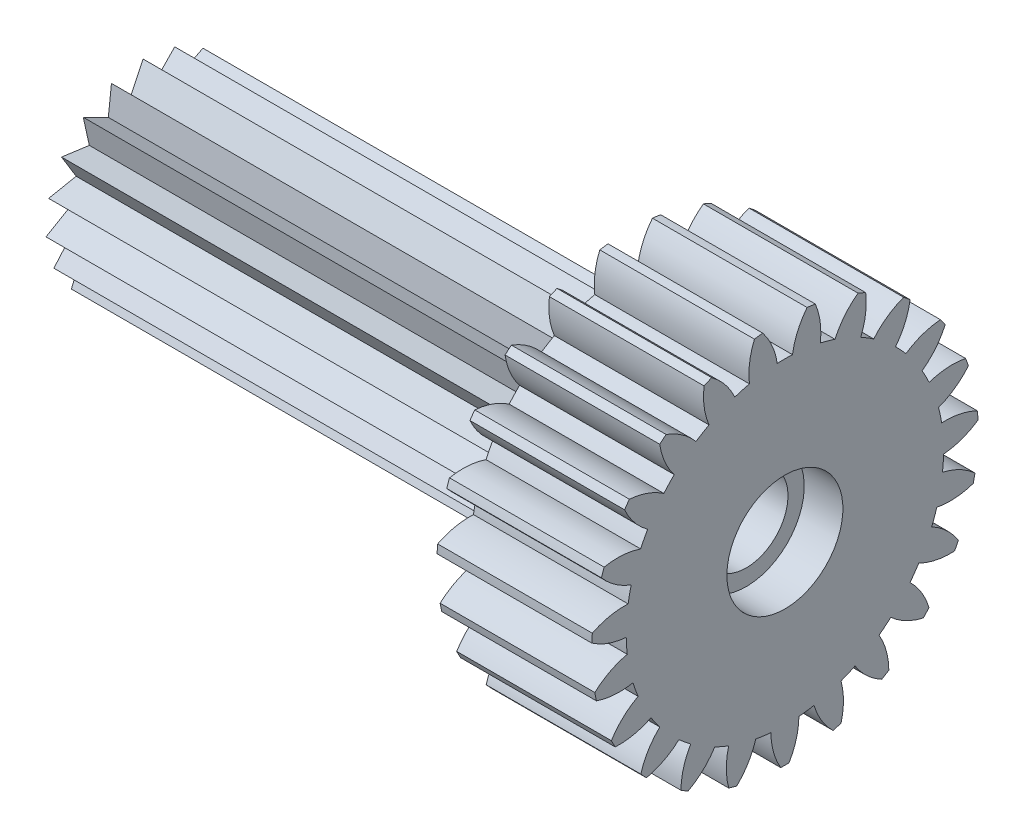
SolidWorks part; units mm, degrees
ref_plane "Plane1" through (0, 0, 0) normal (0, 0, 1) x (1, 0, 0)
ref_plane "Plane2" through (0, 0, 0) normal (0, 1, 0) x (1, 0, 0)
ref_plane "Plane3" through (0, 0, 0) normal (1, 0, 0) x (0, 0, -1)
other "Configuration Table"
sketch "HoldingSke" plane through (0, 0, 0) normal (0, 1, 0) x (1, 0, 0)
  line L0 (0, 0) -> (467.6165, -198.4914)
  line L1 (-15, 0) -> (100, 0) construction
  line L2 (0, 0) -> (-2.1039, 2.3779)
  line L3 (0, 0) -> (-11.863, 4.5341)
  line L4 (0, 0) -> (7.9495, 3.3744)
  line L5 (0, 0) -> (-47.5972, -17.7524)
  line L6 (0, 0) -> (-7.3695, -4.9722)
  line L7 (-2.1039, 2.3779) -> (8.8308, 51.9871)
  line L8 (-76.2, 54.61) -> (-69.596, 54.61)
  line L9 (-71.009, 38.7566) -> (-53.1078, 45.2721)
  line L10 (-76.2, 71.12) -> (104.1128, 71.12)
  line L11 (0, 0) -> (-8.89, 0)
  line L12 (-76.2, 101.6) -> (-76.1492, 101.6)
  line L13 (24.9733, 27.94) -> (52.9518, 28.4284)
  line L14 (24.9733, 27.94) -> (25.0241, 27.9398)
  line L15 (24.9733, 27.94) -> (100.4021, 29.52)
  circle A0 centre (0, 0) radius 3.175
  circle A1 centre (0, 0) radius 13.0302
  circle A2 centre (0, 0) radius 38.1
  circle A3 centre (0, 0) radius 3.175
  dimension "MHD" = 26.0604
  dimension "Hub_dia" = 76.2
  dimension "Bore" = 6.35
  dimension "MBD" = 6.35
  dimension "Num_teeth" = 23
  dimension "Pitch" = 508
  dimension "Overall_len" = 50.8
  dimension "Show_teeth" = 23
  dimension "Thickness" = 8.89
  dimension "OAL" = 50.8001
  dimension "T_dim" = 6.604
  dimension "Ap" = 20
  dimension "H" = 19.05
  dimension "Pitch_radius" = 180.3128
  dimension "Width" = 8.89
  dimension "Backlash" = 0.0508
  dimension "Addendum_fac" = 1
  dimension "Dedendum_fac" = 1.2
  dimension "Clearance_fac" = 0.2
  dimension "Dedendum_add" = 0.0508
sketch "BasProSke" plane through (0, 0, 0) normal (0, 1, 0) x (1, 0, 0)
  line L0 (-10, 0) -> (60, 0) construction
  line L1 (0, 0) -> (0, 15.875)
  line L2 (0, 0) -> (12.7, 0)
  line L3 (12.7, 0) -> (12.7, 15.875)
  line L4 (12.7, 15.875) -> (0, 15.875)
  dimension "Thickness" = 12.7
  dimension "Diameter" = 31.75
revolve "Base-Revolve" add sketch "BasProSke" angle 360 about L0
sketch "TooCutSke" plane through (0, 0, 0) normal (1, 0, 0) x (0, 0, -1)
  line L1 (0, 0) -> (0, 107) construction
  line L2 (0, 0) -> (-1.0855, 14.5646) construction
  line L3 (0, 0) -> (-3.9697, 28.882) construction
  line L4 (-1.0855, 14.5646) -> (-1.9849, 14.441) construction
  arc A0 (0.6246, 13.0152) -> (-0.6246, 13.0152) centre (0, 0) ccw
  arc A1 (1.8419, 15.7934) -> (-1.8419, 15.7934) centre (0, 0) ccw
  circle A2 centre (0, 0) radius 14.605 construction
  circle A3 centre (0, 0) radius 13.7242 construction
  arc A4 (-0.6246, 13.0152) -> (-1.8419, 15.7934) centre (-6.4007, 12.1402) ccw
  arc A5 (1.8419, 15.7934) -> (0.6246, 13.0152) centre (6.4007, 12.1402) ccw
  dimension "Root_dia" = 26.0604
  dimension "Overcut_dia" = 31.8008
  dimension "Pitch_dia" = 29.21
  dimension "Base_dia" = 27.4484
  dimension "Flank_rad" = 5.842
  dimension "Half_ang" = 7.826
  dimension "Half_CT" = 0.9078
extrude "ToothCut" cut sketch "TooCutSke" along normal through all
fillet "Breaks" [suppressed] radius 0.0254
fillet "RootFillets" [suppressed] radius 0.3048
pattern_circular "TeethCuts" count 23 every 15.652 about axis through (-10, 0, 0) along (1, 0, 0) of "ToothCut", "RootFillets", "Breaks"
sketch "HubNeaOneSke" plane through (0, 0, 0) normal (-1, 0, 0) x (0, 0, 1)
  circle A0 centre (0, 0) radius 13.0302
  dimension "Diameter" = 26.0604
extrude "HubNearOne" [suppressed] add sketch "HubNeaOneSke" along normal blind 38.1001
sketch "HubNeaBotSke" plane through (0, 0, 0) normal (-1, 0, 0) x (0, 0, 1)
  circle A0 centre (0, 0) radius 13.0302
  dimension "Diameter" = 26.0604
extrude "HubNearBoth" [suppressed] add sketch "HubNeaBotSke" along normal blind 19.05
ref_plane "FarPln" through (12.7, 0, 0) normal (1, 0, 0) x (0, 0, -1)
sketch "HubFarSke" plane through (12.7, 0, 0) normal (1, 0, 0) x (0, 0, -1)
  circle A0 centre (0, 0) radius 13.0302
  dimension "Diameter" = 26.0604
extrude "HubFar" [suppressed] add sketch "HubFarSke" along normal blind 19.05
sketch "BorSke" plane through (0, 0, 0) normal (1, 0, 0) x (0, 0, -1)
  circle A0 centre (0, 0) radius 4.7625
  dimension "Diameter" = 9.525
extrude "Bore" cut sketch "BorSke" along normal mid plane 101.6001
sketch "KeySke" plane through (0, 0, 0) normal (1, 0, 0) x (0, 0, -1)
  line L0 (-0.127, 0) -> (-0.127, 3.429)
  line L1 (-0.127, 3.429) -> (0.127, 3.429)
  line L2 (0.127, 3.429) -> (0.127, 0)
  line L3 (0, 0) -> (0, 34) construction
  line L4 (-0.127, 0) -> (0.127, 0)
  dimension "Offset" = 3.429
  dimension "Width" = 0.254
extrude "Keyway" [suppressed] cut sketch "KeySke" along normal mid plane 101.6001
pattern_circular "Keyway2" [suppressed] count 2 every 90 about axis through (-10, 0, 0) along (1, 0, 0)
sketch "Sketch2" plane through (0, 0, 0) normal (-1, 0, 0) x (0, 0, 1)
  line L0 (2.5976, 7.5665) -> (2.8557, 5.2768)
  line L1 (-0.9876, 5.9182) -> (0, 8)
  line L2 (0, 8) -> (0.9876, 5.9182)
  line L3 (0.9876, 5.9182) -> (2.5976, 7.5665)
  line L4 (4.9137, 6.3131) -> (4.4143, 4.0637)
  line L5 (2.8557, 5.2768) -> (4.9137, 6.3131)
  line L6 (6.6973, 4.3756) -> (5.4946, 2.4102)
  line L7 (4.4143, 4.0637) -> (6.6973, 4.3756)
  line L8 (7.7552, 1.9639) -> (5.9795, 0.4955)
  line L9 (5.4946, 2.4102) -> (7.7552, 1.9639)
  line L10 (7.9727, -0.6606) -> (5.8164, -1.4729)
  line L11 (5.9795, 0.4955) -> (7.9727, -0.6606)
  line L12 (7.3262, -3.2136) -> (5.023, -3.2817)
  line L13 (5.8164, -1.4729) -> (7.3262, -3.2136)
  line L14 (5.8858, -5.4183) -> (3.6853, -4.7348)
  line L15 (5.023, -3.2817) -> (5.8858, -5.4183)
  line L16 (3.8076, -7.0358) -> (1.9482, -5.6749)
  line L17 (3.6853, -4.7348) -> (3.8076, -7.0358)
  line L18 (1.3168, -7.8909) -> (0, -6)
  line L19 (1.9482, -5.6749) -> (1.3168, -7.8909)
  line L20 (-1.3168, -7.8909) -> (-1.9482, -5.6749)
  line L21 (0, -6) -> (-1.3168, -7.8909)
  line L22 (-3.8076, -7.0358) -> (-3.6853, -4.7348)
  line L23 (-1.9482, -5.6749) -> (-3.8076, -7.0358)
  line L24 (-5.8858, -5.4183) -> (-5.023, -3.2817)
  line L25 (-3.6853, -4.7348) -> (-5.8858, -5.4183)
  line L26 (-7.3262, -3.2136) -> (-5.8164, -1.4729)
  line L27 (-5.023, -3.2817) -> (-7.3262, -3.2136)
  line L28 (-7.9727, -0.6606) -> (-5.9795, 0.4955)
  line L29 (-5.8164, -1.4729) -> (-7.9727, -0.6606)
  line L30 (-7.7552, 1.9639) -> (-5.4946, 2.4102)
  line L31 (-5.9795, 0.4955) -> (-7.7552, 1.9639)
  line L32 (-6.6973, 4.3756) -> (-4.4143, 4.0637)
  line L33 (-5.4946, 2.4102) -> (-6.6973, 4.3756)
  line L34 (-4.9137, 6.3131) -> (-2.8557, 5.2768)
  line L35 (-4.4143, 4.0637) -> (-4.9137, 6.3131)
  line L36 (-2.5976, 7.5665) -> (-0.9876, 5.9182)
  line L37 (-2.8557, 5.2768) -> (-2.5976, 7.5665)
  circle A0 centre (0, 0) radius 6 construction
  circle A1 centre (0, 0) radius 3.429
  point P62 (0, 0)
  dimension "D1" = 12
  dimension "D4" = 6.858
  dimension "D2" = 8
  dimension "D3" = 19
extrude "Boss-Extrude1" add sketch "Sketch2" along normal blind 40 and the other way blind 9.525
sketch "Sketch3" plane through (-40, 0, 0) normal (-1, 0, 0) x (0, 0, 1)
  circle A0 centre (0, 0) radius 4.7625
  dimension "D1" = 9.525
extrude "Cut-Extrude1" cut sketch "Sketch3" against normal blind 3.175
equation "' \"Pitch@HoldingSke\" = 4"
equation "' \"Num_teeth@HoldingSke\" = 12"
equation "' \"Ap@HoldingSke\" =  20"
equation "' \"Ap@HoldingSke\" = 20"
equation "' \"Width@HoldingSke\" = 0.5"
equation "' \"Hub_dia@HoldingSke\"= 1"
equation "' \"Hub_dia@HoldingSke\" = 1"
equation "' \"Overall_len@HoldingSke\" = 1.0"
equation "' \"Bore@HoldingSke\" = 0.75"
equation "' \"T_dim@HoldingSke\" = 0.85"
equation "' \"Width@KeySke\" = 0.25"
equation "' \"Show_teeth@HoldingSke\" = 13"
equation "' \"Backlash@HoldingSke\" = 0.009"
equation "' \"Addendum_fac@HoldingSke\" = 1.0"
equation "' \"Dedendum_fac@HoldingSke\" = 1.25"
equation "' \"Dedendum_add@HoldingSke\" = 0.00005"
equation "' \"Clearance_fac@HoldingSke\" = 0.25"
equation "' \"Pitch@HoldingSke\" = 0.5"
equation "' \"Num_teeth@HoldingSke\" = 23"
equation "' \"Show_teeth@HoldingSke\" = 23"
equation "' \"Backlash@HoldingSke\" = 0.0375"
equation "\"Overcut_dia@TooCutSke\" = (\"Num_teeth@HoldingSke\" + 2 * \"Addendum_fac@HoldingSke\") / \"Pitch@HoldingSke\" + 0.002"
equation "\"Pitch_dia@TooCutSke\" = \"Num_teeth@HoldingSke\" / \"Pitch@HoldingSke\""
equation "\"Base_dia@TooCutSke\" = \"Num_teeth@HoldingSke\" / \"Pitch@HoldingSke\" * cos((\"Ap@HoldingSke\"  * 3.14159265 / 180))"
equation "\"Root_dia@TooCutSke\" = (\"Num_teeth@HoldingSke\" + 2) / \"Pitch@HoldingSke\" - 2 * (\"Addendum_fac@HoldingSke\" + \"Dedendum_fac@HoldingSke\") / \"Pitch@HoldingSke\" - \"Dedendum_add@HoldingSke\" * 2"
equation "\"Half_ang@TooCutSke\" = 180 / \"Num_teeth@HoldingSke\""
equation "\"Half_CT@TooCutSke\" = \"Num_teeth@HoldingSke\" / \"Pitch@HoldingSke\" * sin((3.14159265 / 2 / \"Num_teeth@HoldingSke\")) / 2 - 7 * \"Backlash@HoldingSke\" / 4"
equation "\"Flank_rad@TooCutSke\" = \"Num_teeth@HoldingSke\" / \"Pitch@HoldingSke\" / 5"
equation "\"Radius@RootFillets\" = \"Clearance_fac@HoldingSke\" / \"Pitch@HoldingSke\" + \"Dedendum_add@HoldingSke\""
equation "\"Break_rad@Breaks\" = 0.02 / \"Pitch@HoldingSke\""
equation "\"Thickness@HoldingSke\" = \"Width@HoldingSke\""
equation "\"OAL@HoldingSke\" = \"Thickness@HoldingSke\""
equation "\"MHD@HoldingSke\" = (\"Num_teeth@HoldingSke\" + 2) / \"Pitch@HoldingSke\" - 2 * (\"Addendum_fac@HoldingSke\" + \"Dedendum_fac@HoldingSke\")  / \"Pitch@HoldingSke\" - \"Dedendum_add@HoldingSke\" * 2"
equation "\"MBD@HoldingSke\" = (\"Num_teeth@HoldingSke\" + 2) / \"Pitch@HoldingSke\" - 2 * (\"Addendum_fac@HoldingSke\" + \"Dedendum_fac@HoldingSke\")  / \"Pitch@HoldingSke\" - \"Dedendum_add@HoldingSke\" * 2 - 0.002"
equation "\"MHD@HoldingSke\" = ((sgn( \"MHD@HoldingSke\" - \"Hub_dia@HoldingSke\" )-1)*( \"MHD@HoldingSke\" - \"Hub_dia@HoldingSke\" ))/-2+ \"Hub_dia@HoldingSke\""
equation "\"MBD@HoldingSke\" = ((sgn( \"MBD@HoldingSke\" - \"Bore@HoldingSke\" )-1)*( \"MBD@HoldingSke\" - \"Bore@HoldingSke\" ))/-2+ \"Bore@HoldingSke\""
equation "\"OAL@HoldingSke\" = ((sgn( \"OAL@HoldingSke\" - \"Overall_len@HoldingSke\" )+1)*( \"OAL@HoldingSke\" - \"Overall_len@HoldingSke\" ))/2 + \"Overall_len@HoldingSke\" + 0.000002"
equation "\"Num_teeth@TeethCuts\" = int( \"Show_teeth@HoldingSke\" ) + 1"
equation "\"Num_teeth@TeethCuts\" = ((sgn( \"Num_teeth@TeethCuts\" - \"Num_teeth@HoldingSke\" )-1)*( \"Num_teeth@TeethCuts\" - \"Num_teeth@HoldingSke\" ))/-2+ \"Num_teeth@HoldingSke\""
equation "\"Num_teeth@TeethCuts\" = ((sgn( \"Num_teeth@TeethCuts\" - 2.0)+1)*( \"Num_teeth@TeethCuts\" - 2.0))/2 +2.0"
equation "\"Angle@TeethCuts\" = 360.0 / \"Num_teeth@HoldingSke\""
equation "\"Diameter@BasProSke\" = (\"Num_teeth@HoldingSke\" + 2 * \"Addendum_fac@HoldingSke\") / \"Pitch@HoldingSke\""
equation "' \"Fillet_rad@BasProSke\" =  \"Thickness@HoldingSke\" * 0.05"
equation "' \"Fillet_rad@BasProSke\" = \"Thickness@HoldingSke\" * 0.05"
equation "\"MHD@HoldingSke\" = ((sgn( \"MHD@HoldingSke\" - \"Root_dia@TooCutSke\" )-1)*( \"MHD@HoldingSke\" - \"Root_dia@TooCutSke\" ))/-2+ \"Root_dia@TooCutSke\""
equation "\"Diameter@HubNeaOneSke\" = \"MHD@HoldingSke\""
equation "\"Length@HubNearOne\" = \"OAL@HoldingSke\" - \"Thickness@BasProSke\""
equation "\"Diameter@HubNeaBotSke\" = \"MHD@HoldingSke\""
equation "\"Length@HubNearBoth\" = ( \"OAL@HoldingSke\" - \"Thickness@BasProSke\" ) / 2.0"
equation "\"Thickness@FarPln\" = \"Thickness@BasProSke\""
equation "\"Diameter@HubFarSke\" = \"MHD@HoldingSke\""
equation "\"Length@HubFar\" = ( \"OAL@HoldingSke\" - \"Thickness@BasProSke\" ) / 2.0"
equation "\"D1@Bore\" = \"OAL@HoldingSke\" * 2.0"
equation "\"D1@Keyway\" = \"OAL@HoldingSke\" * 2.0"
equation "\"Offset@KeySke\" = \"T_dim@HoldingSke\" - \"MBD@HoldingSke\" / 2.0"
